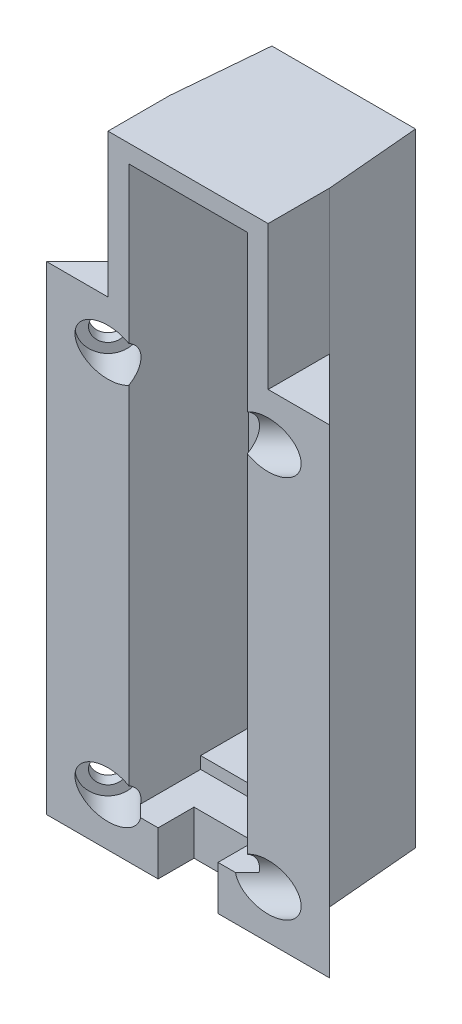
SolidWorks part; units mm, degrees
ref_plane "前视基准面" through (0, 0, 0) normal (0, 0, 1) x (1, 0, 0)
ref_plane "上视基准面" through (0, 0, 0) normal (0, 1, 0) x (1, 0, 0)
ref_plane "右视基准面" through (0, 0, 0) normal (1, 0, 0) x (0, 0, -1)
sketch "草图1" plane through (0, 0, 0) normal (0, 1, 0) x (1, 0, 0)
  line L3 (6.6879, 5.1371) -> (6, 13)
  line L4 (6, 13) -> (-6, 13)
  line L5 (0, 13) -> (0, -8.0101) construction
  line L6 (-6.6879, 5.1371) -> (-6, 13)
  line L7 (6.6879, 5.1371) -> (11.825, 0)
  line L8 (11.825, 0) -> (-11.825, 0)
  line L9 (-6.6879, 5.1371) -> (-11.825, 0)
  point P10 (0, 0)
  point P12 (0, 0)
  dimension "D1" = 135
  dimension "D2" = 12
  dimension "D3" = 95
  dimension "D4" = 13
  dimension "D5" = 23.65
extrude "凸台-拉伸1" add sketch "草图1" along normal blind 40
sketch "草图2" plane through (0, 40, 0) normal (0, 1, 0) x (1, 0, 0)
  line L0 (6.6879, 5.1371) -> (6, 13) construction
  line L1 (6, 13) -> (-6, 13) construction
  line L2 (-6, 13) -> (-6.6879, 5.1371) construction
  line L3 (6.6879, 5.1371) -> (6, 13)
  line L4 (6, 13) -> (-6, 13)
  line L5 (-6, 13) -> (-6.6879, 5.1371)
  line L6 (-6.6879, 5.1371) -> (-6.6879, 0)
  line L8 (-6.6879, 0) -> (6.6879, 0)
  line L9 (6.6879, 0) -> (6.6879, 5.1371)
  line L10 (-11.825, 0) -> (11.825, 0) construction
extrude "凸台-拉伸2" add sketch "草图2" along normal blind 12
chamfer "倒角1" [suppressed] distance 1.1 angle 45
sketch "草图3" plane through (0, 0, 0) normal (0, 0, 1) x (1, 0, 0)
  line L0 (0, 0) -> (0, 27.35) construction
  line L2 (-6.6879, 52) -> (6.6879, 52) construction
  line L3 (-4.95, 4.7) -> (4.95, 4.7)
  line L4 (-4.95, 4.7) -> (-4.95, 50)
  line L5 (-4.95, 50) -> (4.95, 50)
  line L6 (4.95, 4.7) -> (4.95, 50)
  line L7 (-4.95, 4.7) -> (4.95, 50) construction
  line L8 (-4.95, 50) -> (4.95, 4.7) construction
  dimension "D1" = 45.3
  dimension "D2" = 9.9
  dimension "D3" = 2
extrude "切除-拉伸1" cut sketch "草图3" against normal offset from surface (10 mm away) 3 up to face at (0, 26, -13)
sketch "草图4" plane through (0, 0, -10) normal (0, 0, 1) x (1, 0, 0)
  line L0 (0, 50) -> (0, 4.7) construction
  line L1 (-4.95, 50) -> (4.95, 50) construction
  line L2 (4.95, 4.7) -> (-4.95, 4.7) construction
  line L4 (-1.75, 9.85) -> (1.75, 9.85)
  line L5 (-1.75, 9.85) -> (-1.75, 44.85)
  line L6 (-1.75, 44.85) -> (1.75, 44.85)
  line L7 (1.75, 9.85) -> (1.75, 44.85)
  line L8 (-1.75, 9.85) -> (1.75, 44.85) construction
  line L9 (-1.75, 44.85) -> (1.75, 9.85) construction
  point P6 (0, 27.35)
  dimension "D1" = 35
  dimension "D2" = 3.5
extrude "切除-拉伸2" cut sketch "草图4" against normal through all
sketch "草图5" plane through (0, 0, 0) normal (0, 0, 1) x (1, 0, 0)
  line L0 (4.95, 50) -> (4.95, 4.7) construction
  line L1 (-4.95, 50) -> (4.95, 50)
  line L2 (-4.95, 50) -> (-4.95, 50.5)
  line L3 (-4.95, 50.5) -> (4.95, 50.5)
  line L4 (4.95, 50) -> (4.95, 50.5)
  line L6 (-4.95, 50) -> (-4.95, 4.7) construction
  line L7 (-4.95, 4.7) -> (4.95, 4.7)
  line L8 (-4.95, 4.7) -> (-4.95, 3.7)
  line L9 (-4.95, 3.7) -> (4.95, 3.7)
  line L10 (4.95, 4.7) -> (4.95, 3.7)
  line L11 (-4.95, 4.7) -> (4.95, 4.7) construction
  dimension "D1" = 0.5
  dimension "D2" = 1
extrude "切除-拉伸3" cut sketch "草图5" against normal offset from surface (6 mm away) 4 up to face at (0, 27.35, -10)
sketch "草图6" plane through (0, 0, -10) normal (0, 0, 1) x (1, 0, 0)
  line L0 (1.75, 27.35) -> (19.3892, 27.35) construction
  line L1 (1.75, 9.85) -> (1.75, 44.85) construction
  line L2 (0, 44.85) -> (0, 9.85) construction
  line L3 (1.75, 44.85) -> (-1.75, 44.85) construction
  line L4 (-1.75, 9.85) -> (1.75, 9.85) construction
  circle A0 centre (0, 47.85) radius 1.15
  circle A1 centre (0, 6.85) radius 1.15
  dimension "D1" = 41
  dimension "D2" = 2.3
extrude "切除-拉伸4" cut sketch "草图6" against normal through all
sketch "草图7" plane through (0, 0, -13) normal (0, 0, -1) x (-1, 0, 0)
  circle A0 centre (0, 47.85) radius 1.95
  circle A1 centre (0, 6.85) radius 1.95
  dimension "D1" = 3.9
extrude "切除-拉伸5" cut sketch "草图7" against normal blind 1.2
sketch "草图10" plane through (-5.9125, 0, -5.9125) normal (-0.7071, 0, -0.7071) x (-0.7071, 0, 0.7071)
  line L0 (4.7291, 40) -> (4.7291, 0) construction
  line L1 (1.0966, 40) -> (8.3615, 40) construction
  line L2 (1.0966, 0) -> (8.3615, 0) construction
  line L3 (4.7291, 20) -> (20.0718, 20) construction
  circle A0 centre (4.7291, 36) radius 1.15
  circle A1 centre (4.7291, 4) radius 1.15
  dimension "D1" = 2.3
  dimension "D2" = 4
extrude "切除-拉伸6" cut sketch "草图10" against normal blind 10
sketch "草图11" plane through (-5.9125, 0, -5.9125) normal (-0.7071, 0, -0.7071) x (-0.7071, 0, 0.7071)
  circle A0 centre (4.7291, 36) radius 1.95
  circle A1 centre (4.7291, 4) radius 1.95
  dimension "D1" = 3.9
extrude "切除-拉伸7" cut sketch "草图11" against normal blind 10 from offset 1 offset against normal yes
mirror "镜向1" about plane through (0, 0, 0) normal (1, 0, 0) of "切除-拉伸7", "切除-拉伸6"
sketch "草图12" plane through (0, 3.7, 0) normal (0, 1, 0) x (1, 0, 0)
  line L0 (0, 0) -> (0, 3.3681) construction
  line L1 (-3.963, 0) -> (3.963, 0) construction
  line L3 (-2.5, 3) -> (2.5, 3)
  line L4 (-2.5, 3) -> (-2.5, 0)
  line L5 (-2.5, 0) -> (2.5, 0)
  line L6 (2.5, 3) -> (2.5, 0)
  line L7 (-2.5, 3) -> (2.5, 0) construction
  line L8 (-2.5, 0) -> (2.5, 3) construction
  point P4 (0, 1.5)
  dimension "D1" = 3
  dimension "D2" = 5
extrude "切除-拉伸8" cut sketch "草图12" against normal through all
